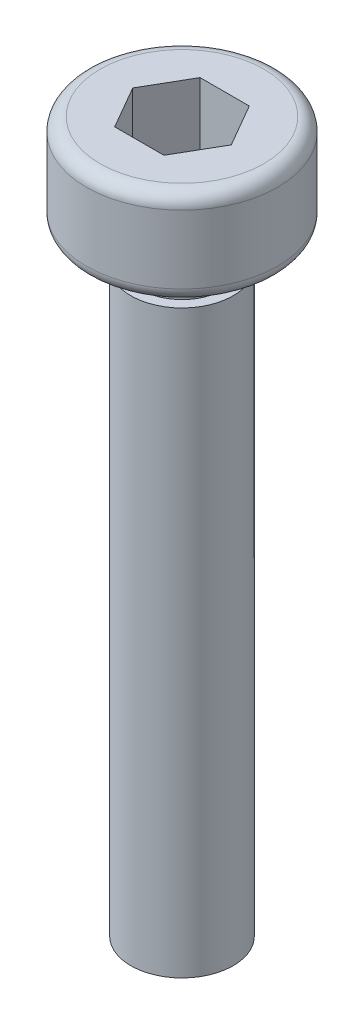
SolidWorks part; units mm, degrees
material "AISI 304"
ref_plane "前视基准面" through (0, 0, 0) normal (0, 0, 1) x (1, 0, 0)
ref_plane "上视基准面" through (0, 0, 0) normal (0, 1, 0) x (1, 0, 0)
ref_plane "右视基准面" through (0, 0, 0) normal (1, 0, 0) x (0, 0, -1)
sketch "草图1" plane through (0, 0, 0) normal (0, 0, 1) x (1, 0, 0)
  line L0 (0, 0) -> (0, 20.8) construction
  line L1 (0, 20.8) -> (-2.4, 20.8)
  line L2 (-2.8, 20.4) -> (-2.8, 18.4)
  line L3 (-2.4, 18) -> (-1.2, 18)
  line L4 (-1.2, 18) -> (-1.2, 17)
  line L5 (-1.2, 17) -> (-1.5, 17)
  line L6 (-1.5, 17) -> (-1.5, 0)
  line L7 (-1.5, 0) -> (0, 0)
  line L8 (0, 0) -> (0, 20.8)
  arc A0 (-2.8, 18.4) -> (-2.4, 18) centre (-2.4, 18.4) ccw
  arc A1 (-2.4, 20.8) -> (-2.8, 20.4) centre (-2.4, 20.4) ccw
  point P11 (-2.8, 18)
  point P14 (-2.8, 20.8)
  dimension "D7" = 0.4
  dimension "D1" = 18
  dimension "D2" = 2.8
  dimension "D3" = 5.6
  dimension "D4" = 3
  dimension "D5" = 1
  dimension "D6" = 1.2
revolve "旋转1" add sketch "草图1" angle 360 about L0
cosmetic thread "装饰螺纹线1"
sketch "草图2" plane through (0, 20.8, 0) normal (0, 1, 0) x (1, 0, 0)
  line L1 (-0.7217, 1.25) -> (-1.4434, 0)
  line L2 (-1.4434, 0) -> (-0.7217, -1.25)
  line L3 (-0.7217, -1.25) -> (0.7217, -1.25)
  line L4 (0.7217, -1.25) -> (1.4434, 0)
  line L5 (1.4434, 0) -> (0.7217, 1.25)
  line L6 (0.7217, 1.25) -> (-0.7217, 1.25)
  circle A0 centre (0, 0) radius 1.25 construction
  dimension "D1" = 2.5
extrude "切除-拉伸1" cut sketch "草图2" against normal blind 2
